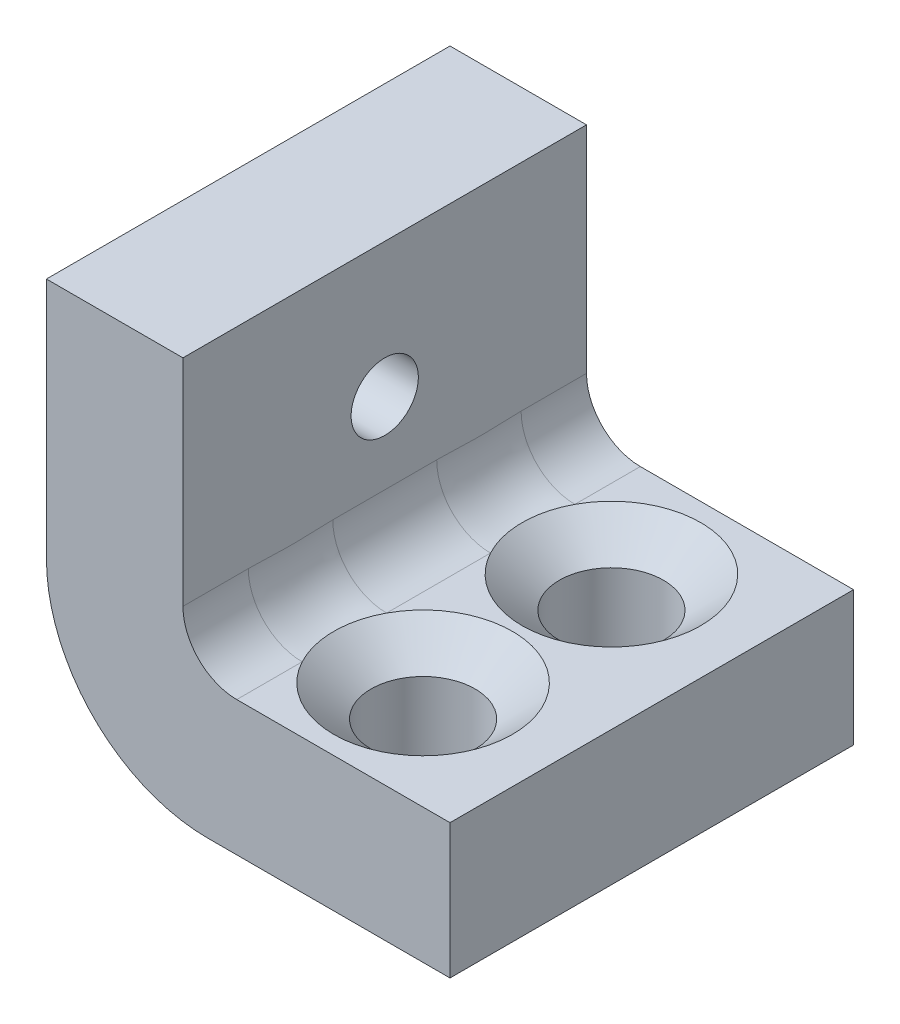
SolidWorks part; units mm, degrees
material "ABS"
ref_plane "Front Plane" through (0, 0, 0) normal (0, 0, 1) x (1, 0, 0)
ref_plane "Top Plane" through (0, 0, 0) normal (0, 1, 0) x (1, 0, 0)
ref_plane "Right Plane" through (0, 0, 0) normal (1, 0, 0) x (0, 0, -1)
sketch "Sketch1" plane through (0, 0, 0) normal (0, 1, 0) x (1, 0, 0)
  line L1 (0, 0) -> (19.05, 0)
  line L2 (0, 0) -> (0, 19.05)
  line L3 (0, 19.05) -> (19.05, 19.05)
  line L4 (19.05, 0) -> (19.05, 19.05)
  dimension "D1" = 19.05
  dimension "D2" = 19.05
extrude "Boss-Extrude1" add sketch "Sketch1" along normal blind 6.35
sketch "Sketch2" plane through (0, 6.35, 0) normal (0, 1, 0) x (1, 0, 0)
  line L0 (19.05, 19.05) -> (0, 19.05) construction
  line L1 (0, 0) -> (6.4441, 0)
  line L2 (0, 0) -> (0, 19.05)
  line L3 (0, 19.05) -> (6.4441, 19.05)
  line L4 (6.4441, 0) -> (6.4441, 19.05)
extrude "Boss-Extrude2" add sketch "Sketch2" along normal blind 12.7
hole_wizard "CSK for #8 Flat Head Machine Screw (100)1" positions "Sketch3" profile "Sketch4" countersink size "#8" standard "ANSI Inch"
sketch "Sketch3" plane through (0, 6.35, 0) normal (0, 1, 0) x (1, 0, 0)
  line L0 (19.05, 0) -> (19.05, 19.05) construction
  line L1 (19.05, 19.05) -> (6.4441, 19.05) construction
  line L2 (6.4441, 0) -> (19.05, 0) construction
  point P0 (12.7, 13.97)
  point P2 (12.7, 5.08)
  dimension "D1" = 6.35
  dimension "D2" = 5.08
  dimension "D3" = 5.08
  dimension "D4" = 6.35
sketch "Sketch4" plane through (12.7, 6.35, -13.97) normal (1, 0, 0) x (0, 0, 1)
  line L0 (0, 0) -> (0, 24.8446)
  line L1 (0, 24.8446) -> (2.4574, 23.368)
  line L2 (2.4574, 23.368) -> (2.4574, 1.4759)
  line L3 (2.4574, 1.4759) -> (4.2164, 0)
  line L5 (4.2164, 0) -> (0, 0)
  line L6 (-2.4574, 1.4759) -> (-4.2164, 0) construction
  line L10 (0, 24.8446) -> (-2.4575, 23.368) construction
  line L11 (0, -6.35) -> (0, 107.95) construction
  dimension "Hole Dia." = 4.9149
  dimension "Hole Depth" = 23.368
  dimension "Near C'Sink Dia." = 8.4328
  dimension "Near C'Sink Angle" = 100
  dimension "Drill Angle" = 118
sketch "Sketch5" plane through (6.4441, 0, 0) normal (1, 0, 0) x (0, 0, -1)
  line L0 (19.05, 19.05) -> (19.05, 6.35) construction
  line L1 (0, 19.05) -> (19.05, 19.05) construction
  circle A0 centre (9.525, 12.7) radius 1.5875
  dimension "D1" = 3.175
  dimension "D2" = 9.525
  dimension "D3" = 6.35
extrude "Cut-Extrude1" cut sketch "Sketch5" against normal blind 12.7
fillet "Fillet1" radius 2.54 1 edges at (6.4441, 6.35, -9.525)
fillet "Fillet2" radius 7.62 1 edges at (0, 0, -9.525)
